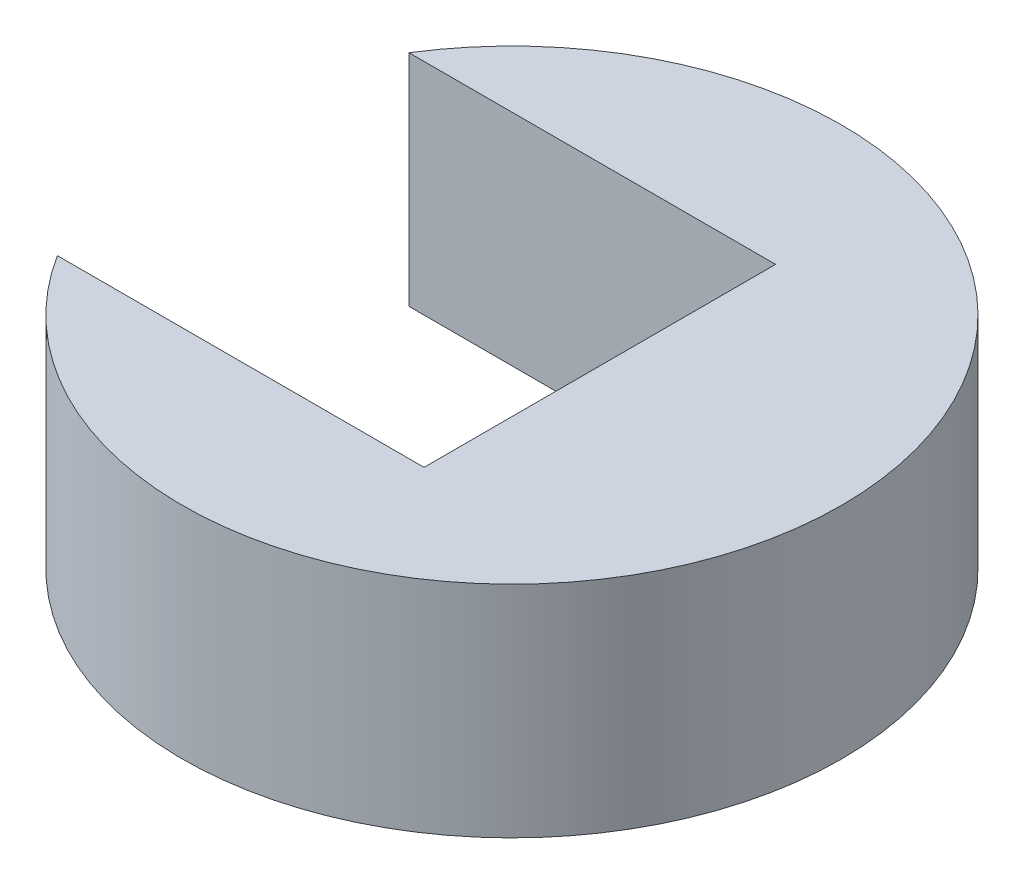
SolidWorks part; units mm, degrees
ref_plane "Front Plane" through (0, 0, 0) normal (0, 0, 1) x (1, 0, 0)
ref_plane "Top Plane" through (0, 0, 0) normal (0, 1, 0) x (1, 0, 0)
ref_plane "Right Plane" through (0, 0, 0) normal (1, 0, 0) x (0, 0, -1)
sketch "Sketch1" plane through (0, 0, 0) normal (0, 1, 0) x (1, 0, 0)
  line L0 (0, 0) -> (4, 0) construction
  circle A0 centre (0, 0) radius 7.5
  circle A1 centre (4, 0) radius 15
  dimension "D1" = 15
  dimension "D2" = 30
  dimension "D3" = 4
extrude "Boss-Extrude1" add sketch "Sketch1" along normal blind 10
sketch "Sketch2" plane through (0, 0, 0) normal (0, -1, 0) x (1, 0, 0)
  line L0 (0, 0) -> (-4.5, 0) construction
  line L1 (8, -8) -> (-17, -8)
  line L2 (8, -8) -> (8, 8)
  line L3 (8, 8) -> (-17, 8)
  line L4 (-17, -8) -> (-17, 8)
  line L5 (8, -8) -> (-17, 8) construction
  line L6 (8, 8) -> (-17, -8) construction
  point P0 (-4.5, 0)
  dimension "D1" = 8
  dimension "D2" = 16
  dimension "D3" = 25
extrude "Cut-Extrude1" cut sketch "Sketch2" against normal through all
